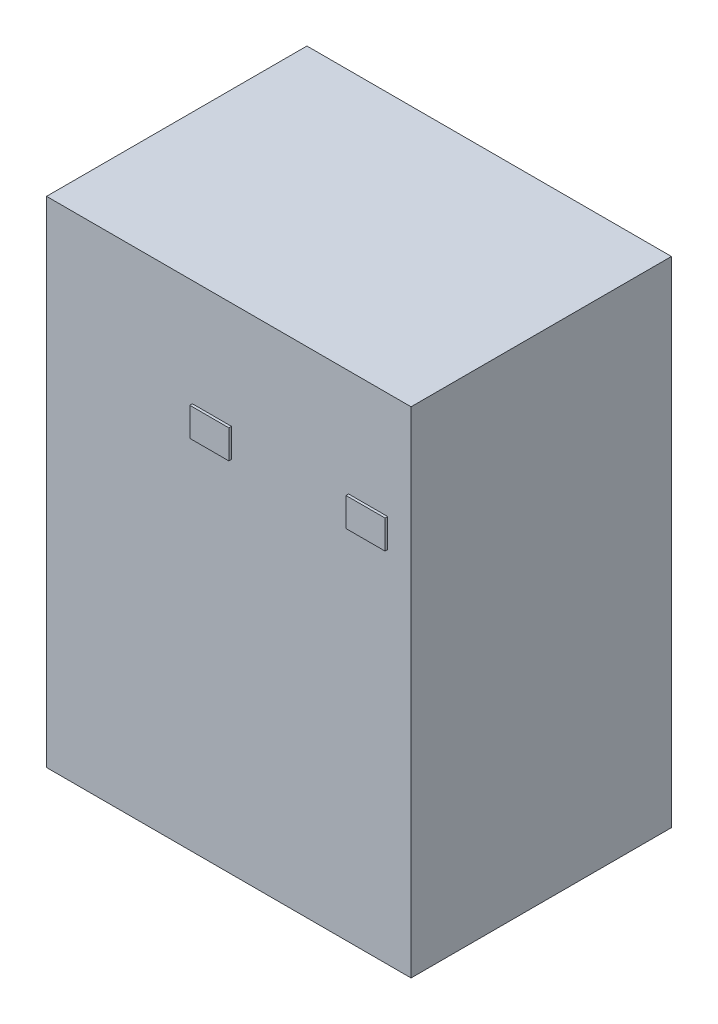
SolidWorks part; units mm, degrees
ref_plane "Front" through (0, 0, 0) normal (0, 0, 1) x (1, 0, 0)
ref_plane "Top" through (0, 0, 0) normal (0, 1, 0) x (1, 0, 0)
ref_plane "Right" through (0, 0, 0) normal (1, 0, 0) x (0, 0, -1)
sketch "Sketch1" plane through (0, 0, 0) normal (0, 0, 1) x (1, 0, 0)
  line L1 (0, 0) -> (140, 0)
  line L2 (0, 0) -> (0, -190)
  line L3 (0, -190) -> (140, -190)
  line L4 (140, 0) -> (140, -190)
  dimension "D1" = 140
  dimension "D2" = 190
extrude "Boss-Extrude1" add sketch "Sketch1" along normal blind 100
sketch "Sketch2" plane through (0, 0, 100) normal (0, 0, 1) x (1, 0, 0)
  line L0 (140, -190) -> (140, 0) construction
  line L1 (116, -41) -> (131, -41)
  line L2 (116, -41) -> (116, -52)
  line L3 (116, -52) -> (131, -52)
  line L4 (131, -41) -> (131, -52)
  line L5 (56, -41) -> (71, -41)
  line L6 (56, -41) -> (56, -52)
  line L7 (56, -52) -> (71, -52)
  line L8 (71, -41) -> (71, -52)
  line L10 (140, 0) -> (0, 0) construction
  dimension "D1" = 15
  dimension "D2" = 9
  dimension "D3" = 69
  dimension "D4" = 15
  dimension "D5" = 11
  dimension "D6" = 11
  dimension "D7" = 41
  dimension "D8" = 41
extrude "Boss-Extrude2" add sketch "Sketch2" along normal blind 1
